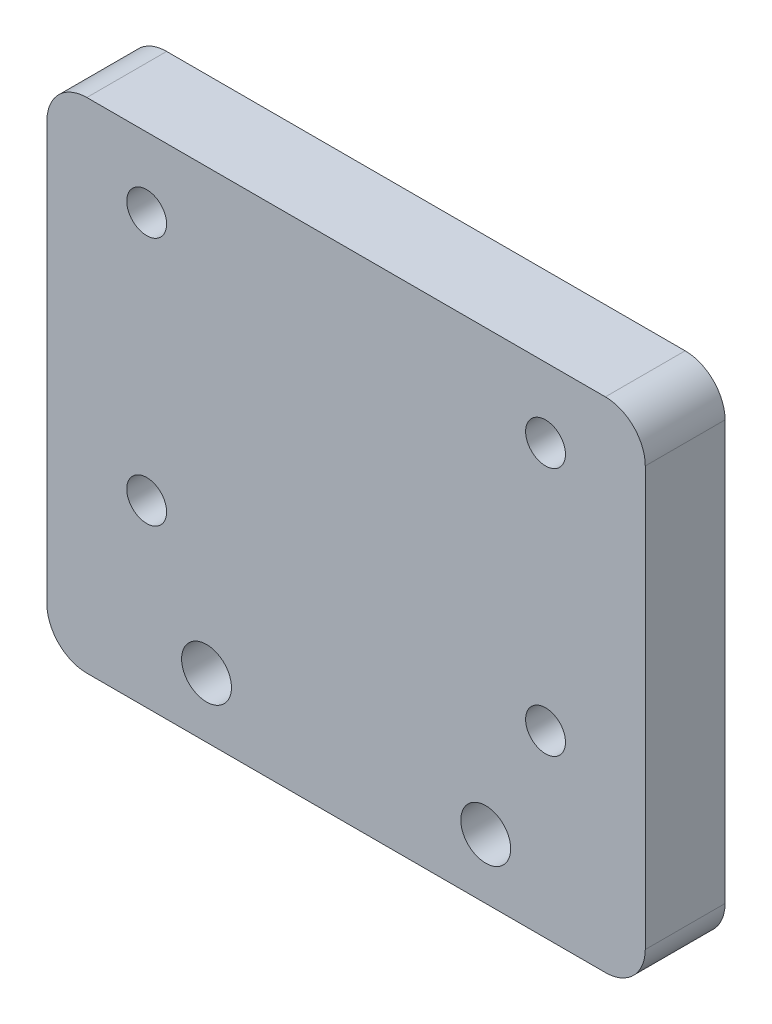
SolidWorks part; units mm, degrees
ref_plane "正面" through (0, 0, 0) normal (0, 0, 1) x (1, 0, 0)
ref_plane "平面" through (0, 0, 0) normal (0, 1, 0) x (1, 0, 0)
ref_plane "右側面" through (0, 0, 0) normal (1, 0, 0) x (0, 0, -1)
sketch "ｽｹｯﾁ1" plane through (0, 0, 0) normal (0, 0, 1) x (1, 0, 0)
  line L1 (-15, -12.5) -> (15, -12.5)
  line L2 (-15, -12.5) -> (-15, 12.5)
  line L3 (-15, 12.5) -> (15, 12.5)
  line L4 (15, -12.5) -> (15, 12.5)
  line L5 (-15, -12.5) -> (15, 12.5) construction
  line L6 (-15, 12.5) -> (15, -12.5) construction
  circle A0 centre (-7, -9.5) radius 1.25
  circle A1 centre (7, -9.5) radius 1.25
  circle A2 centre (-10, -3.5) radius 1
  circle A3 centre (-10, 9) radius 1
  circle A4 centre (10, 9) radius 1
  circle A5 centre (10, -3.5) radius 1
  point P0 (0, 0)
  dimension "D5" = 2.5
  dimension "D7" = 5
  dimension "D8" = 9
  dimension "D9" = 2
  dimension "D1" = 25
  dimension "D2" = 30
  dimension "D3" = 8
  dimension "D4" = 3
  dimension "D6" = 8
  dimension "D10" = 5
  dimension "D11" = 12.5
extrude "ﾎﾞｽ - 押し出し1" add sketch "ｽｹｯﾁ1" along normal blind 4
fillet "ﾌｨﾚｯﾄ1" radius 2 4 edges at (15, -12.5, 2) (-15, -12.5, 2) (15, 12.5, 2) (-15, 12.5, 2)
